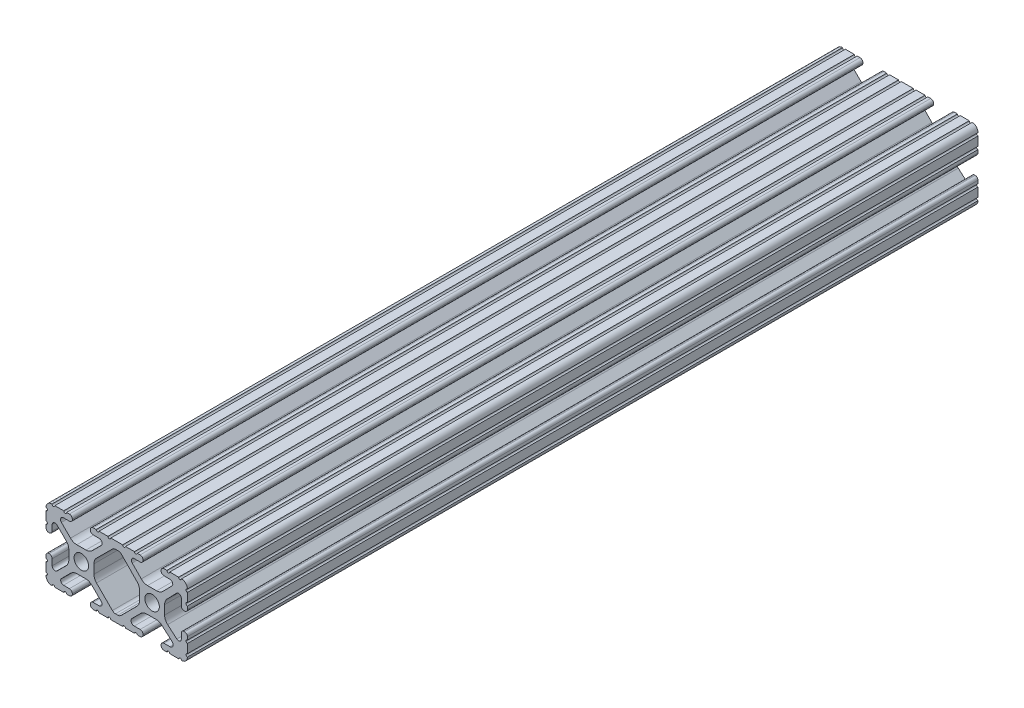
SolidWorks part; units mm, degrees
ref_plane "Front Plane" through (0, 0, 0) normal (0, 0, 1) x (1, 0, 0)
ref_plane "Top Plane" through (0, 0, 0) normal (0, 1, 0) x (1, 0, 0)
ref_plane "Right Plane" through (0, 0, 0) normal (1, 0, 0) x (0, 0, -1)
sketch "Sketch1" plane through (0, 0, 0) normal (0, 0, 1) x (1, 0, 0)
  line L0 (-7.2595, -3.8694) -> (-1.5457, -9.5728)
  line L1 (-8.1915, 1.6223) -> (-8.1915, -1.6223)
  line L2 (-1.504, 9.5765) -> (-7.252, 3.8768)
  line L3 (0.5515, 10.033) -> (-0.3952, 10.033)
  line L4 (7.2829, 3.8459) -> (1.6756, 9.5611)
  line L5 (8.1915, -1.6223) -> (8.1915, 1.6223)
  line L6 (1.5457, -9.5728) -> (7.2595, -3.8694)
  line L7 (-0.4332, -10.033) -> (0.4332, -10.033)
  line L8 (18.0171, 12.7) -> (16.9875, 12.7)
  line L9 (15.9385, 11.651) -> (15.9385, 11.5392)
  line L10 (16.9875, 10.4902) -> (19.1164, 10.4902)
  line L11 (19.8441, 8.7652) -> (16.619, 5.4551)
  line L12 (14.3449, 4.4958) -> (11.0833, 4.4958)
  line L13 (8.817, 5.4472) -> (5.5642, 8.7627)
  line L14 (6.2894, 10.4902) -> (8.4125, 10.4902)
  line L15 (9.4615, 11.5392) -> (9.4615, 11.651)
  line L16 (8.4125, 12.7) -> (7.3829, 12.7)
  line L17 (6.3669, 12.7) -> (3.1496, 12.7)
  line L18 (2.1336, 12.7) -> (-2.1336, 12.7)
  line L19 (-3.1496, 12.7) -> (-6.3669, 12.7)
  line L20 (-7.3829, 12.7) -> (-8.4125, 12.7)
  line L21 (-9.4615, 11.651) -> (-9.4615, 11.5392)
  line L22 (-8.4125, 10.4902) -> (-6.2836, 10.4902)
  line L23 (-5.5326, 8.6661) -> (-8.81, 5.4163)
  line L24 (-11.0455, 4.4958) -> (-14.3545, 4.4958)
  line L25 (-16.59, 5.4163) -> (-19.8674, 8.6661)
  line L26 (-19.1164, 10.4902) -> (-16.9875, 10.4902)
  line L27 (-15.9385, 11.5392) -> (-15.9385, 11.651)
  line L28 (-16.9875, 12.7) -> (-18.0171, 12.7)
  line L29 (-19.0331, 12.7) -> (-22.2504, 12.7)
  line L30 (-25.4, 9.5504) -> (-25.4, 6.3331)
  line L31 (-25.4, 5.3171) -> (-25.4, 4.2375)
  line L32 (-24.401, 3.2385) -> (-24.2392, 3.2385)
  line L33 (-23.1902, 4.2875) -> (-23.1902, 6.3347)
  line L34 (-21.434, 7.0665) -> (-18.148, 3.8082)
  line L35 (-17.2085, 1.5536) -> (-17.2085, -1.6952)
  line L36 (-18.1405, -3.9423) -> (-21.4316, -7.2274)
  line L37 (-23.1902, -6.498) -> (-23.1902, -4.2875)
  line L38 (-24.2392, -3.2385) -> (-24.351, -3.2385)
  line L39 (-25.4, -4.2875) -> (-25.4, -5.3171)
  line L40 (-25.4, -6.3331) -> (-25.4, -9.5504)
  line L41 (-22.2504, -12.7) -> (-19.0331, -12.7)
  line L42 (-18.0171, -12.7) -> (-16.9875, -12.7)
  line L43 (-15.9384, -11.651) -> (-15.9384, -11.5392)
  line L44 (-16.9875, -10.4902) -> (-19.1164, -10.4902)
  line L45 (-19.8341, -8.7551) -> (-16.4966, -5.4237)
  line L46 (-14.2536, -4.4958) -> (-11.1464, -4.4958)
  line L47 (-8.9034, -5.4237) -> (-5.5659, -8.7551)
  line L48 (-6.2836, -10.4902) -> (-8.4125, -10.4902)
  line L49 (-9.4616, -11.5392) -> (-9.4616, -11.651)
  line L50 (-8.4125, -12.7) -> (-7.3829, -12.7)
  line L51 (-6.3669, -12.7) -> (-3.1496, -12.7)
  line L52 (-2.1336, -12.7) -> (2.1336, -12.7)
  line L53 (3.1496, -12.7) -> (6.3669, -12.7)
  line L54 (7.3829, -12.7) -> (8.4125, -12.7)
  line L55 (9.4616, -11.651) -> (9.4616, -11.5392)
  line L56 (8.4125, -10.4902) -> (6.2894, -10.4902)
  line L57 (5.4807, -8.5353) -> (8.5979, -5.4237)
  line L58 (10.8409, -4.4958) -> (14.1026, -4.4958)
  line L59 (16.1879, -5.2766) -> (19.8682, -8.4822)
  line L60 (19.1164, -10.4902) -> (16.9875, -10.4902)
  line L61 (15.9384, -11.5392) -> (15.9384, -11.651)
  line L62 (16.9875, -12.7) -> (18.0171, -12.7)
  line L63 (19.0331, -12.7) -> (22.2504, -12.7)
  line L64 (25.4, -9.5504) -> (25.4, -6.3331)
  line L65 (25.4, -5.3171) -> (25.4, -4.2375)
  line L66 (24.401, -3.2385) -> (24.1892, -3.2385)
  line L67 (23.1902, -4.2375) -> (23.1902, -6.1559)
  line L68 (21.584, -6.8869) -> (18.2982, -4.025)
  line L69 (17.2085, -1.6308) -> (17.2085, 1.6308)
  line L70 (18.1094, 3.8465) -> (21.5263, 7.3534)
  line L71 (23.1902, 6.6769) -> (23.1902, 4.2375)
  line L72 (24.1892, 3.2385) -> (24.401, 3.2385)
  line L73 (25.4, 4.2375) -> (25.4, 5.3171)
  line L74 (25.4, 6.3332) -> (25.4, 9.5504)
  line L75 (22.2504, 12.7) -> (19.0331, 12.7)
  circle A0 centre (-12.7, 0) radius 2.6035
  circle A1 centre (12.7, 0) radius 2.6035
  arc A2 (-1.5457, -9.5728) -> (-0.4332, -10.033) centre (-0.4332, -8.4582) ccw
  arc A3 (-8.1915, -1.6223) -> (-7.2595, -3.8694) centre (-5.0165, -1.6223) ccw
  arc A4 (-7.252, 3.8768) -> (-8.1915, 1.6223) centre (-5.0165, 1.6223) ccw
  arc A5 (-0.3952, 10.033) -> (-1.504, 9.5765) centre (-0.3952, 8.4582) ccw
  arc A6 (1.6756, 9.5611) -> (0.5515, 10.033) centre (0.5515, 8.4582) ccw
  arc A7 (8.1915, 1.6223) -> (7.2829, 3.8459) centre (5.0165, 1.6223) ccw
  arc A8 (7.2595, -3.8694) -> (8.1915, -1.6223) centre (5.0165, -1.6223) ccw
  arc A9 (0.4332, -10.033) -> (1.5457, -9.5728) centre (0.4332, -8.4582) ccw
  arc A10 (18.0171, 12.7) -> (19.0331, 12.7) centre (18.5251, 12.7) ccw
  arc A11 (16.9875, 12.7) -> (15.9385, 11.651) centre (16.9875, 11.651) ccw
  arc A12 (15.9385, 11.5392) -> (16.9875, 10.4902) centre (16.9875, 11.5392) ccw
  arc A13 (19.8441, 8.7652) -> (19.1164, 10.4902) centre (19.1164, 9.4742) ccw
  arc A14 (14.3449, 4.4958) -> (16.619, 5.4551) centre (14.3449, 7.6708) ccw
  arc A15 (8.817, 5.4472) -> (11.0833, 4.4958) centre (11.0833, 7.6708) ccw
  arc A16 (6.2894, 10.4902) -> (5.5642, 8.7627) centre (6.2894, 9.4742) ccw
  arc A17 (8.4125, 10.4902) -> (9.4615, 11.5392) centre (8.4125, 11.5392) ccw
  arc A18 (9.4615, 11.651) -> (8.4125, 12.7) centre (8.4125, 11.651) ccw
  arc A19 (6.3669, 12.7) -> (7.3829, 12.7) centre (6.8749, 12.7) ccw
  arc A20 (2.1336, 12.7) -> (3.1496, 12.7) centre (2.6416, 12.7) ccw
  arc A21 (-3.1496, 12.7) -> (-2.1336, 12.7) centre (-2.6416, 12.7) ccw
  arc A22 (-7.3829, 12.7) -> (-6.3669, 12.7) centre (-6.8749, 12.7) ccw
  arc A23 (-8.4125, 12.7) -> (-9.4615, 11.651) centre (-8.4125, 11.651) ccw
  arc A24 (-9.4615, 11.5392) -> (-8.4125, 10.4902) centre (-8.4125, 11.5392) ccw
  arc A25 (-5.5326, 8.6661) -> (-6.2836, 10.4902) centre (-6.2836, 9.4235) ccw
  arc A26 (-11.0455, 4.4958) -> (-8.81, 5.4163) centre (-11.0455, 7.6708) ccw
  arc A27 (-16.59, 5.4163) -> (-14.3545, 4.4958) centre (-14.3545, 7.6708) ccw
  arc A28 (-19.1164, 10.4902) -> (-19.8674, 8.6661) centre (-19.1164, 9.4235) ccw
  arc A29 (-16.9875, 10.4902) -> (-15.9385, 11.5392) centre (-16.9875, 11.5392) ccw
  arc A30 (-15.9385, 11.651) -> (-16.9875, 12.7) centre (-16.9875, 11.651) ccw
  arc A31 (-19.0331, 12.7) -> (-18.0171, 12.7) centre (-18.5251, 12.7) ccw
  arc A32 (-23.2664, 12.6998) -> (-22.2504, 12.7) centre (-22.7584, 12.7) ccw
  arc A33 (-23.2664, 12.6998) -> (-25.3998, 10.5664) centre (-23.2918, 10.5918) ccw
  arc A34 (-25.4, 9.5504) -> (-25.3998, 10.5664) centre (-25.4, 10.0584) ccw
  arc A35 (-25.4, 5.3171) -> (-25.4, 6.3331) centre (-25.4, 5.8251) ccw
  arc A36 (-25.4, 4.2375) -> (-24.401, 3.2385) centre (-24.401, 4.2375) ccw
  arc A37 (-24.2392, 3.2385) -> (-23.1902, 4.2875) centre (-24.2392, 4.2875) ccw
  arc A38 (-21.434, 7.0665) -> (-23.1902, 6.3347) centre (-22.1596, 6.3347) ccw
  arc A39 (-17.2085, 1.5536) -> (-18.148, 3.8082) centre (-20.3835, 1.5536) ccw
  arc A40 (-18.1405, -3.9423) -> (-17.2085, -1.6952) centre (-20.3835, -1.6952) ccw
  arc A41 (-23.1902, -6.498) -> (-21.4316, -7.2274) centre (-22.1596, -6.498) ccw
  arc A42 (-23.1902, -4.2875) -> (-24.2392, -3.2385) centre (-24.2392, -4.2875) ccw
  arc A43 (-24.351, -3.2385) -> (-25.4, -4.2875) centre (-24.351, -4.2875) ccw
  arc A44 (-25.4, -6.3331) -> (-25.4, -5.3171) centre (-25.4, -5.8251) ccw
  arc A45 (-25.3998, -10.5664) -> (-25.4, -9.5504) centre (-25.4, -10.0584) ccw
  arc A46 (-25.3998, -10.5664) -> (-23.2664, -12.6998) centre (-23.2918, -10.5918) ccw
  arc A47 (-22.2504, -12.7) -> (-23.2664, -12.6998) centre (-22.7584, -12.7) ccw
  arc A48 (-18.0171, -12.7) -> (-19.0331, -12.7) centre (-18.5251, -12.7) ccw
  arc A49 (-16.9875, -12.7) -> (-15.9384, -11.651) centre (-16.9875, -11.651) ccw
  arc A50 (-15.9384, -11.5392) -> (-16.9875, -10.4902) centre (-16.9875, -11.5392) ccw
  arc A51 (-19.8341, -8.7551) -> (-19.1164, -10.4902) centre (-19.1164, -9.4742) ccw
  arc A52 (-14.2536, -4.4958) -> (-16.4966, -5.4237) centre (-14.2536, -7.6708) ccw
  arc A53 (-8.9034, -5.4237) -> (-11.1464, -4.4958) centre (-11.1464, -7.6708) ccw
  arc A54 (-6.2836, -10.4902) -> (-5.5659, -8.7551) centre (-6.2836, -9.4742) ccw
  arc A55 (-8.4125, -10.4902) -> (-9.4616, -11.5392) centre (-8.4125, -11.5392) ccw
  arc A56 (-9.4616, -11.651) -> (-8.4125, -12.7) centre (-8.4125, -11.651) ccw
  arc A57 (-6.3669, -12.7) -> (-7.3829, -12.7) centre (-6.8749, -12.7) ccw
  arc A58 (-2.1336, -12.7) -> (-3.1496, -12.7) centre (-2.6416, -12.7) ccw
  arc A59 (3.1496, -12.7) -> (2.1336, -12.7) centre (2.6416, -12.7) ccw
  arc A60 (7.3829, -12.7) -> (6.3669, -12.7) centre (6.8749, -12.7) ccw
  arc A61 (8.4125, -12.7) -> (9.4616, -11.651) centre (8.4125, -11.651) ccw
  arc A62 (9.4616, -11.5392) -> (8.4125, -10.4902) centre (8.4125, -11.5392) ccw
  arc A63 (5.4807, -8.5353) -> (6.2894, -10.4902) centre (6.2894, -9.3455) ccw
  arc A64 (10.8409, -4.4958) -> (8.5979, -5.4237) centre (10.8409, -7.6708) ccw
  arc A65 (16.1879, -5.2766) -> (14.1026, -4.4958) centre (14.1026, -7.6708) ccw
  arc A66 (19.1164, -10.4902) -> (19.8682, -8.4822) centre (19.1164, -9.3455) ccw
  arc A67 (16.9875, -10.4902) -> (15.9384, -11.5392) centre (16.9875, -11.5392) ccw
  arc A68 (15.9384, -11.651) -> (16.9875, -12.7) centre (16.9875, -11.651) ccw
  arc A69 (19.0331, -12.7) -> (18.0171, -12.7) centre (18.5251, -12.7) ccw
  arc A70 (23.2664, -12.6998) -> (22.2504, -12.7) centre (22.7584, -12.7) ccw
  arc A71 (23.2664, -12.6998) -> (25.3998, -10.5664) centre (23.2918, -10.5918) ccw
  arc A72 (25.4, -9.5504) -> (25.3998, -10.5664) centre (25.4, -10.0584) ccw
  arc A73 (25.4, -5.3171) -> (25.4, -6.3331) centre (25.4, -5.8251) ccw
  arc A74 (25.4, -4.2375) -> (24.401, -3.2385) centre (24.401, -4.2375) ccw
  arc A75 (24.1892, -3.2385) -> (23.1902, -4.2375) centre (24.1892, -4.2375) ccw
  arc A76 (21.584, -6.8869) -> (23.1902, -6.1559) centre (22.2207, -6.1559) ccw
  arc A77 (17.2085, -1.6308) -> (18.2982, -4.025) centre (20.3835, -1.6308) ccw
  arc A78 (18.1094, 3.8465) -> (17.2085, 1.6308) centre (20.3835, 1.6308) ccw
  arc A79 (23.1902, 6.6769) -> (21.5263, 7.3534) centre (22.2207, 6.6769) ccw
  arc A80 (23.1902, 4.2375) -> (24.1892, 3.2385) centre (24.1892, 4.2375) ccw
  arc A81 (24.401, 3.2385) -> (25.4, 4.2375) centre (24.401, 4.2375) ccw
  arc A82 (25.4, 6.3332) -> (25.4, 5.3171) centre (25.4, 5.8251) ccw
  arc A83 (25.3998, 10.5664) -> (25.4, 9.5504) centre (25.4, 10.0584) ccw
  arc A84 (25.3998, 10.5664) -> (23.2664, 12.6998) centre (23.2918, 10.5918) ccw
  arc A85 (22.2504, 12.7) -> (23.2664, 12.6998) centre (22.7584, 12.7) ccw
  point P248 (0, 10.033)
extrude "Boss-Extrude1" add sketch "Sketch1" along normal mid plane 283.9752
